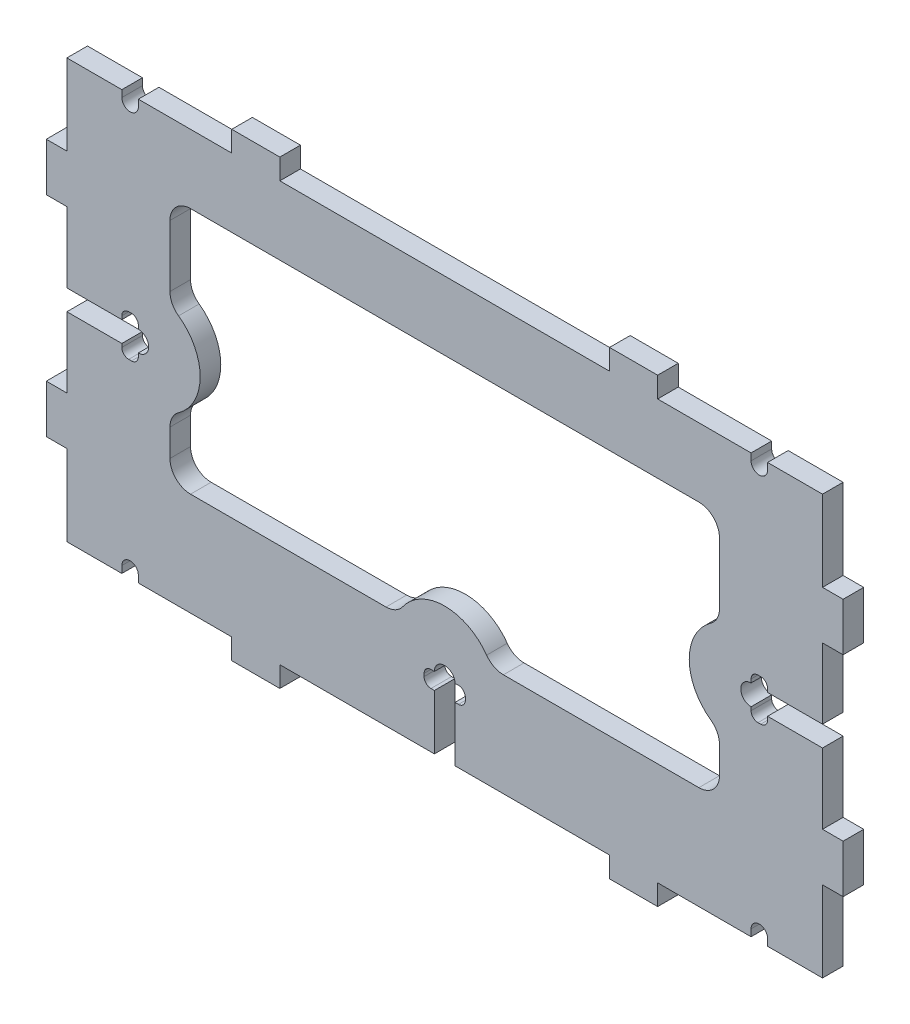
SolidWorks part; units mm, degrees
material "Acrylic (Medium-high impact)"
ref_plane "Front Plane" through (0, 0, 0) normal (0, 0, 1) x (1, 0, 0)
ref_plane "Top Plane" through (0, 0, 0) normal (0, 1, 0) x (1, 0, 0)
ref_plane "Right Plane" through (0, 0, 0) normal (1, 0, 0) x (0, 0, -1)
sketch "Sketch1" plane through (0, 0, 0) normal (0, 0, 1) x (1, 0, 0)
  line L0 (0, 30.5) -> (0, -30.5) construction
  line L1 (-55, 30.5) -> (55, 30.5)
  line L2 (-55, 30.5) -> (-55, -30.5)
  line L3 (-55, -30.5) -> (55, -30.5)
  line L4 (55, 30.5) -> (55, -30.5)
  line L5 (-55, 0) -> (55, 0) construction
  line L6 (-55, 0) -> (-55, -1.5) construction
  line L7 (-55, -1.5) -> (-47, -1.5)
  line L8 (-47, -1.5) -> (-47, -3)
  line L9 (-47, -3) -> (-44.6, -3)
  line L10 (-44.6, -3) -> (-44.6, -1.5)
  line L11 (-44.6, 3) -> (-47, 3)
  line L12 (-47, 3) -> (-47, 1.5)
  line L13 (-47, 1.5) -> (-55, 1.5)
  line L14 (-55, 1.5) -> (-55, -1.5)
  line L15 (-44.6, 1.5) -> (-44.6, 3)
  line L16 (44.6, 1.5) -> (44.6, 3)
  line L17 (47, 3) -> (47, 1.5)
  line L18 (44.6, 3) -> (47, 3)
  line L19 (44.6, -3) -> (44.6, -1.5)
  line L20 (47, -3) -> (44.6, -3)
  line L21 (47, -1.5) -> (47, -3)
  line L22 (47, 1.5) -> (55, 1.5)
  line L23 (55, -1.5) -> (47, -1.5)
  line L24 (55, 1.5) -> (55, -1.5)
  arc A0 (-44.6, -1.5) -> (-44.6, 1.5) centre (-44.6, 0) ccw
  arc A1 (-45.8, 2.9798) -> (-47, 2) centre (-46, 2) ccw
  arc A2 (-44.6, 2) -> (-45.8, 2.9798) centre (-45.6, 2) ccw
  arc A3 (-47, -2) -> (-45.8, -2.9798) centre (-46, -2) ccw
  arc A4 (-45.8, -2.9798) -> (-44.6, -2) centre (-45.6, -2) ccw
  arc A5 (45.8, -2.9798) -> (44.6, -2) centre (45.6, -2) cw
  arc A6 (47, -2) -> (45.8, -2.9798) centre (46, -2) cw
  arc A7 (44.6, 2) -> (45.8, 2.9798) centre (45.6, 2) cw
  arc A8 (45.8, 2.9798) -> (47, 2) centre (46, 2) cw
  arc A9 (44.6, -1.5) -> (44.6, 1.5) centre (44.6, 0) cw
  point P8 (0, 0)
  point P9 (110, 0)
extrude "Boss-Extrude1" add sketch "Sketch1" along normal blind 3 contours L19 A9 L16 L18 L17 L22 L4 L1 L2 L13 L12 L11 L15 A0 L10 L9 L8 L7 L3 L23 L21 L20 | A3 L8 L9 | A4 L9 L10 | A2 L15 L11 | A1 L11 L12 | L20 A5 L19 | L21 A6 L20 | L18 A8 L17 | L16 A7 L18
sketch "Sketch2" plane through (0, 0, 3) normal (0, 0, 1) x (1, 0, 0)
  line L0 (-47, -1.5) -> (-47, -30.5) construction
  line L1 (-55, -30.5) -> (55, -30.5) construction
  line L2 (-47, -30.5) -> (-44.6, -30.5) construction
  line L3 (-44.6, -30.5) -> (-44.6, 30.5) construction
  line L4 (-55, 30.5) -> (55, 30.5) construction
  line L5 (-44.6, 30.5) -> (-47, 30.5) construction
  line L6 (-47, 30.5) -> (-47, -1.5) construction
  line L7 (47, -1.5) -> (47, -30.5) construction
  line L8 (47, -30.5) -> (44.6, -30.5) construction
  line L9 (44.6, -30.5) -> (44.6, 30.5) construction
  line L10 (44.6, 30.5) -> (47, 30.5) construction
  line L11 (47, 30.5) -> (47, -1.5) construction
  line L12 (-45.8, 30.5) -> (-45.8, 29.5) construction
  line L13 (-45.8, -30.5) -> (-45.8, -29.5) construction
  line L14 (45.8, -30.5) -> (45.8, -29.5) construction
  line L15 (45.8, 30.5) -> (45.8, 29.5) construction
  line L16 (-47, 29.5) -> (-47, 30.5)
  line L17 (-47, 30.5) -> (-44.6, 30.5)
  line L18 (-44.6, 30.5) -> (-44.6, 29.5)
  line L19 (-47, -29.5) -> (-47, -30.5)
  line L20 (-47, -30.5) -> (-44.6, -30.5)
  line L21 (-44.6, -30.5) -> (-44.6, -29.5)
  line L22 (44.6, -29.5) -> (44.6, -30.5)
  line L23 (44.6, -30.5) -> (47, -30.5)
  line L24 (47, -30.5) -> (47, -29.5)
  line L25 (44.6, 29.5) -> (44.6, 30.5)
  line L26 (44.6, 30.5) -> (47, 30.5)
  line L27 (47, 30.5) -> (47, 29.5)
  arc A0 (44.6, 29.5) -> (47, 29.5) centre (45.8, 29.5) ccw
  arc A1 (-46.4633, -30.5) -> (-45.1367, -30.5) centre (-45.8, -29.5) ccw
  arc A2 (45.1367, -30.5) -> (46.4633, -30.5) centre (45.8, -29.5) ccw
  arc A3 (-47, 29.5) -> (-44.6, 29.5) centre (-45.8, 29.5) ccw
  arc A4 (46.4633, 30.5) -> (45.1367, 30.5) centre (45.8, 29.5) ccw
  arc A5 (47, -29.5) -> (44.6, -29.5) centre (45.8, -29.5) ccw
  arc A6 (-44.6, -29.5) -> (-47, -29.5) centre (-45.8, -29.5) ccw
  arc A7 (-45.1367, 30.5) -> (-46.4633, 30.5) centre (-45.8, 29.5) ccw
  line M11 (55, 30.5) -> (-55, 30.5)
  line M27 (-55, -30.5) -> (55, -30.5)
extrude "Cut-Extrude1" cut sketch "Sketch2" against normal blind 3 contours L25 A0 L27 L26 M11 | L24 A5 L22 L23 M27 | L21 A6 L19 L20 M27 | L16 A3 L18 L17 M11
sketch "Sketch3" plane through (0, 0, 3) normal (0, 0, 1) x (1, 0, 0)
  line L0 (0, -19.4735) -> (0, 19.4735) construction
  line L1 (-44.6, 30.5) -> (44.6, 30.5) construction
  line L2 (-43.1, 0) -> (43.1, 0) construction
  line L3 (0, 30.5) -> (1.5, 30.5)
  line L4 (1.5, 30.5) -> (1.5, 22.5)
  line L5 (1.5, 22.5) -> (3, 22.5)
  line L6 (3, 22.5) -> (3, 20.1)
  line L7 (3, 20.1) -> (1.5, 20.1)
  line L8 (-3, 20.1) -> (-3, 22.5)
  line L9 (-3, 22.5) -> (-1.5, 22.5)
  line L10 (-1.5, 22.5) -> (-1.5, 30.5)
  line L11 (-1.5, 30.5) -> (1.5, 30.5)
  line L12 (-1.5, 20.1) -> (-3, 20.1)
  line L13 (-1.5, -20.1) -> (-3, -20.1)
  line L14 (-1.5, -30.5) -> (1.5, -30.5)
  line L15 (-1.5, -22.5) -> (-1.5, -30.5)
  line L16 (-3, -22.5) -> (-1.5, -22.5)
  line L17 (-3, -20.1) -> (-3, -22.5)
  line L18 (3, -20.1) -> (1.5, -20.1)
  line L19 (3, -22.5) -> (3, -20.1)
  line L20 (1.5, -22.5) -> (3, -22.5)
  line L21 (1.5, -30.5) -> (1.5, -22.5)
  line L22 (0, -30.5) -> (1.5, -30.5)
  arc A0 (-44.6, -1.5) -> (-44.6, 1.5) centre (-44.6, 0) ccw construction
  arc A1 (44.6, 1.5) -> (44.6, -1.5) centre (44.6, 0) ccw construction
  arc A2 (-1.5, 20.1) -> (1.5, 20.1) centre (0, 20.1) ccw
  arc A3 (-1.5, -20.1) -> (1.5, -20.1) centre (0, -20.1) cw
  point P26 (0, 0)
  line M23 (-44.6, -30.5) -> (44.6, -30.5)
extrude "Cut-Extrude3" cut sketch "Sketch3" against normal blind 3 contours A3 L13 L17 L16 L15 L14 L21 L20 L19 L18 M23
fillet "Fillet2" radius 1 4 edges at (-3, -20.1, 1.5) (3, -22.5, 1.5) (3, -20.1, 1.5) (-3, -22.5, 1.5)
sketch "Sketch4" plane through (0, 0, 3) normal (0, 0, 1) x (1, 0, 0)
  line L0 (-55, 1.5) -> (-55, -1.5) construction
  line L1 (55, 1.5) -> (55, -1.5) construction
  line L2 (-1.5, -30.5) -> (1.5, -30.5) construction
  line L3 (-55, 30.5) -> (-40, 30.5)
  line L4 (-44.6, 30.5) -> (44.6, 30.5) construction
  line L5 (-40, 30.5) -> (-40, -15.5)
  line L6 (-40, -15.5) -> (40, -15.5)
  line L7 (40, -15.5) -> (40, 20.5)
  line L8 (40, 20.5) -> (-40, 20.5)
  circle A0 centre (-43.1, 0) radius 7.5
  arc A1 (-44.6, -1.5) -> (-44.6, 1.5) centre (-44.6, 0) ccw construction
  circle A2 centre (0, -18.6) radius 7.5
  arc A3 (1.5, -20.1) -> (-1.5, -20.1) centre (0, -20.1) ccw construction
  circle A4 centre (43.1, 0) radius 7.5
  arc A5 (44.6, 1.5) -> (44.6, -1.5) centre (44.6, 0) ccw construction
extrude "Cut-Extrude4" cut sketch "Sketch4" against normal blind 10 contours A4 L7 L8 L5 A0 L6 A2
fillet "Fillet3" radius 3 10 edges at (40, -6.8293, 1.5) (40, 6.8293, 1.5) (40, -15.5, 1.5) (-6.8293, -15.5, 1.5) (6.8293, -15.5, 1.5) (-40, 6.8293, 1.5) (-40, -6.8293, 1.5) (40, 20.5, 1.5) (-40, -15.5, 1.5) (-40, 20.5, 1.5)
sketch "Sketch5" plane through (0, 0, 3) normal (0, 0, 1) x (1, 0, 0)
  line L0 (-55, -30.5) -> (0, -30.5) construction
  line L1 (0, -30.5) -> (55, -30.5) construction
  line L2 (55, -30.5) -> (55, 0) construction
  line L3 (55, 0) -> (55, 30.5) construction
  line L4 (55, 15.25) -> (58, 15.25) construction
  line L5 (58, 15.25) -> (58, 11.75) construction
  line L6 (58, 11.75) -> (55, 11.75) construction
  line L7 (55, 11.75) -> (55, 18.75) construction
  line L8 (55, 18.75) -> (58, 18.75) construction
  line L9 (58, 18.75) -> (58, 15.25) construction
  line L10 (55, -15.25) -> (58, -15.25) construction
  line L11 (58, -15.25) -> (58, -11.75) construction
  line L12 (58, -11.75) -> (55, -11.75) construction
  line L13 (55, -11.75) -> (55, -18.75) construction
  line L14 (55, -18.75) -> (58, -18.75) construction
  line L15 (58, -18.75) -> (58, -15.25) construction
  line L16 (-27.5, -30.5) -> (-27.5, -33.5) construction
  line L17 (-27.5, -33.5) -> (-24, -33.5) construction
  line L18 (-24, -33.5) -> (-24, -30.5) construction
  line L19 (-24, -30.5) -> (-31, -30.5) construction
  line L20 (-31, -30.5) -> (-31, -33.5) construction
  line L21 (-31, -33.5) -> (-27.5, -33.5) construction
  line L22 (27.5, -30.5) -> (27.5, -33.5) construction
  line L23 (27.5, -33.5) -> (24, -33.5) construction
  line L24 (24, -33.5) -> (24, -30.5) construction
  line L25 (24, -30.5) -> (31, -30.5) construction
  line L26 (31, -30.5) -> (31, -33.5) construction
  line L27 (31, -33.5) -> (27.5, -33.5) construction
  line L28 (-35.6, 0) -> (35.6, 0) construction
  line L29 (0, -11.1) -> (0, 20.5) construction
  line L30 (37, 20.5) -> (-37, 20.5) construction
  line L31 (-58, -18.75) -> (-58, -15.25) construction
  line L32 (-55, -18.75) -> (-58, -18.75) construction
  line L33 (-55, -11.75) -> (-55, -18.75) construction
  line L34 (-58, -11.75) -> (-55, -11.75) construction
  line L35 (-58, -15.25) -> (-58, -11.75) construction
  line L36 (-55, -15.25) -> (-58, -15.25) construction
  line L37 (-58, 18.75) -> (-58, 15.25) construction
  line L38 (-55, 18.75) -> (-58, 18.75) construction
  line L39 (-55, 11.75) -> (-55, 18.75) construction
  line L40 (-58, 11.75) -> (-55, 11.75) construction
  line L41 (-58, 15.25) -> (-58, 11.75) construction
  line L42 (-55, 15.25) -> (-58, 15.25) construction
  line L43 (-55, 0) -> (-55, 30.5) construction
  line L44 (-55, -30.5) -> (-55, 0) construction
  line L45 (31, 33.5) -> (27.5, 33.5) construction
  line L46 (-58, 18.75) -> (-55, 18.75)
  line L47 (-58, 18.75) -> (-58, 11.75)
  line L48 (-58, 11.75) -> (-55, 11.75)
  line L49 (-55, 18.75) -> (-55, 11.75)
  line L50 (-58, -11.75) -> (-55, -11.75)
  line L51 (-58, -11.75) -> (-58, -18.75)
  line L52 (-58, -18.75) -> (-55, -18.75)
  line L53 (-55, -11.75) -> (-55, -18.75)
  line L54 (55, -11.75) -> (58, -11.75)
  line L55 (55, -11.75) -> (55, -18.75)
  line L56 (55, -18.75) -> (58, -18.75)
  line L57 (58, -11.75) -> (58, -18.75)
  line L58 (55, 18.75) -> (58, 18.75)
  line L59 (55, 18.75) -> (55, 11.75)
  line L60 (55, 11.75) -> (58, 11.75)
  line L61 (58, 18.75) -> (58, 11.75)
  line L62 (24, -30.5) -> (31, -30.5)
  line L63 (24, -30.5) -> (24, -33.5)
  line L64 (24, -33.5) -> (31, -33.5)
  line L65 (31, -30.5) -> (31, -33.5)
  line L66 (-31, -30.5) -> (-24, -30.5)
  line L67 (-31, -30.5) -> (-31, -33.5)
  line L68 (-31, -33.5) -> (-24, -33.5)
  line L69 (-24, -30.5) -> (-24, -33.5)
  line L70 (31, 30.5) -> (31, 33.5) construction
  line L71 (24, 30.5) -> (31, 30.5) construction
  line L72 (24, 33.5) -> (24, 30.5) construction
  line L73 (27.5, 33.5) -> (24, 33.5) construction
  line L74 (27.5, 30.5) -> (27.5, 33.5) construction
  line L75 (-31, 33.5) -> (-27.5, 33.5) construction
  line L76 (-31, 30.5) -> (-31, 33.5) construction
  line L77 (-24, 30.5) -> (-31, 30.5) construction
  line L78 (-24, 33.5) -> (-24, 30.5) construction
  line L79 (-27.5, 33.5) -> (-24, 33.5) construction
  line L80 (-27.5, 30.5) -> (-27.5, 33.5) construction
  line L81 (0, 30.5) -> (55, 30.5) construction
  line L82 (-55, 30.5) -> (0, 30.5) construction
  line L83 (-24, 30.5) -> (-24, 33.5)
  line L84 (-31, 33.5) -> (-24, 33.5)
  line L85 (-31, 30.5) -> (-31, 33.5)
  line L86 (-31, 30.5) -> (-24, 30.5)
  line L87 (31, 30.5) -> (31, 33.5)
  line L88 (24, 33.5) -> (31, 33.5)
  line L89 (24, 30.5) -> (24, 33.5)
  line L90 (24, 30.5) -> (31, 30.5)
  arc A0 (-38.7429, -6.1045) -> (-38.7429, 6.1045) centre (-43.1, 0) ccw construction
  arc A1 (38.7429, 6.1045) -> (38.7429, -6.1045) centre (43.1, 0) ccw construction
  arc A2 (6.1045, -14.2429) -> (-6.1045, -14.2429) centre (0, -18.6) ccw construction
extrude "Boss-Extrude2" add sketch "Sketch5" against normal blind 3
